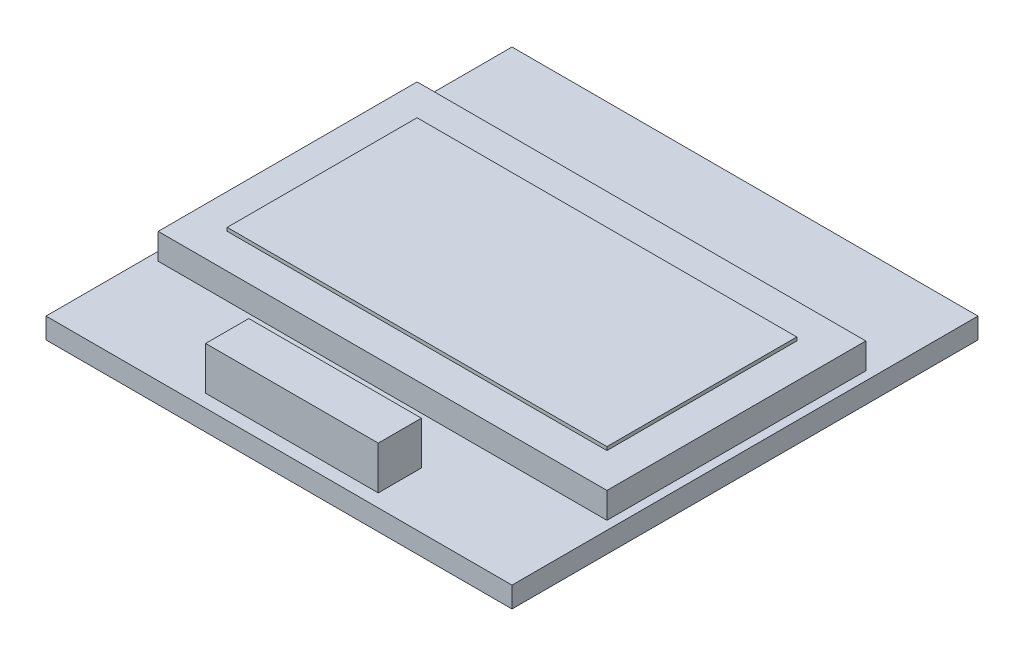
SolidWorks part; units mm, degrees
ref_plane "Front Plane" through (0, 0, 0) normal (0, 0, 1) x (1, 0, 0)
ref_plane "Top Plane" through (0, 0, 0) normal (0, 1, 0) x (1, 0, 0)
ref_plane "Right Plane" through (0, 0, 0) normal (1, 0, 0) x (0, 0, -1)
other "Configuration Table"
sketch "Sketch1" plane through (0, 0, 0) normal (0, 1, 0) x (1, 0, 0)
  line L1 (-13.5, -13.5) -> (13.5, -13.5)
  line L2 (-13.5, -13.5) -> (-13.5, 13.5)
  line L3 (-13.5, 13.5) -> (13.5, 13.5)
  line L4 (13.5, -13.5) -> (13.5, 13.5)
  line L5 (-13.5, -13.5) -> (13.5, 13.5) construction
  line L6 (-13.5, 13.5) -> (13.5, -13.5) construction
extrude "PCB" add sketch "Sketch1" along normal blind 1.2
sketch "Sketch2" plane through (0, 0, 0) normal (0, 1, 0) x (1, 0, 0)
  line L1 (-13, -7.5) -> (13, -7.5)
  line L2 (-13, -7.5) -> (-13, 7.5)
  line L3 (-13, 7.5) -> (13, 7.5)
  line L4 (13, -7.5) -> (13, 7.5)
  line L5 (-13, -7.5) -> (13, 7.5) construction
  line L6 (-13, 7.5) -> (13, -7.5) construction
extrude "Glass" add sketch "Sketch2" along normal blind 1.5 from offset 1.2
sketch "Sketch3" plane through (0, 0, 0) normal (0, 1, 0) x (1, 0, 0)
  line L1 (-11, -5.5) -> (11, -5.5)
  line L2 (-11, -5.5) -> (-11, 5.5)
  line L3 (-11, 5.5) -> (11, 5.5)
  line L4 (11, -5.5) -> (11, 5.5)
  line L5 (-11, -5.5) -> (11, 5.5) construction
  line L6 (-11, 5.5) -> (11, -5.5) construction
extrude "Active_Area" add sketch "Sketch3" along normal blind 0.2 from offset 2.7
sketch "Sketch4" plane through (0, 0, 0) normal (0, 1, 0) x (1, 0, 0)
  line L1 (-5, -12.75) -> (5, -12.75)
  line L2 (-5, -12.75) -> (-5, -10.25)
  line L3 (-5, -10.25) -> (5, -10.25)
  line L4 (5, -12.75) -> (5, -10.25)
  line L5 (-5, -12.75) -> (5, -10.25) construction
  line L6 (-5, -10.25) -> (5, -12.75) construction
extrude "Header" add sketch "Sketch4" along normal blind 2.5 from offset 1.2
equation "\"oled_L\"= 27.0   'ASSUMPTION: OLED board L (PDF fallback)"
equation "\"oled_W\"= 27.0   'ASSUMPTION: OLED board W (PDF fallback)"
equation "\"oled_win_L\"= 22.0   'ASSUMPTION: OLED visible window L (PDF fallback)"
equation "\"oled_win_W\"= 11.0   'ASSUMPTION: OLED visible window W (PDF fallback)"
